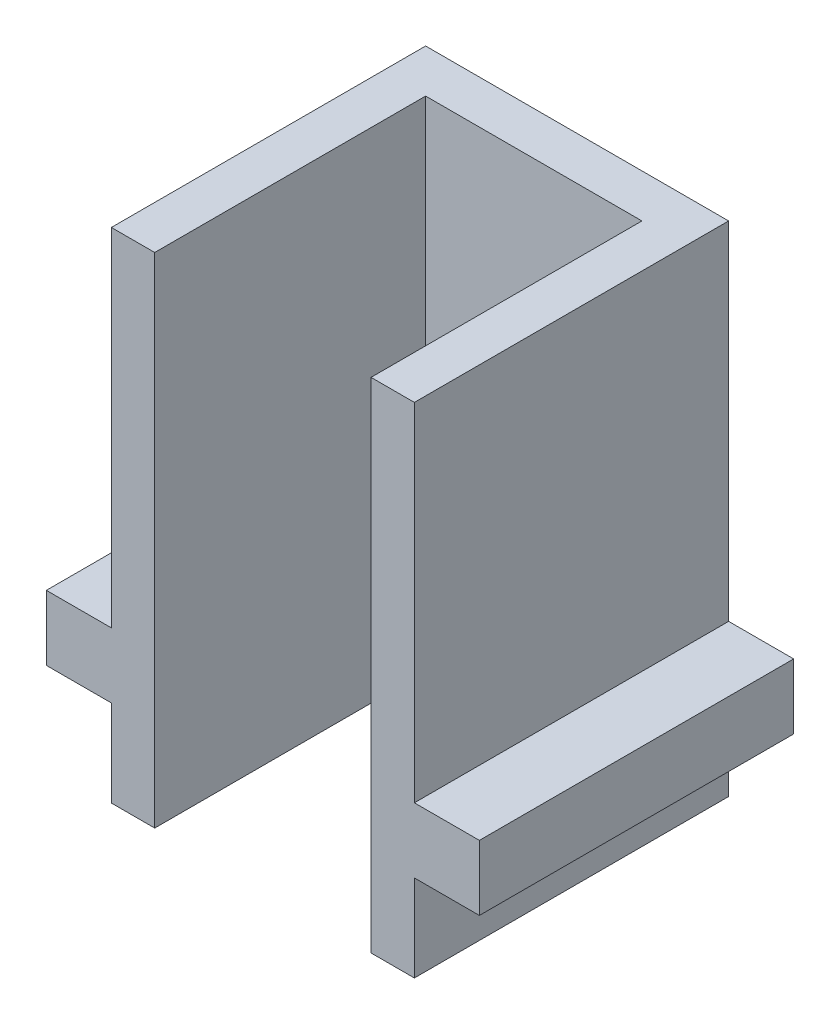
SolidWorks part; units mm, degrees
ref_plane "Front Plane" through (0, 0, 0) normal (0, 0, 1) x (1, 0, 0)
ref_plane "Top Plane" through (0, 0, 0) normal (0, 1, 0) x (1, 0, 0)
ref_plane "Right Plane" through (0, 0, 0) normal (1, 0, 0) x (0, 0, -1)
sketch "Sketch1" plane through (0, 0, 0) normal (0, 1, 0) x (1, 0, 0)
  line L0 (-4.99, 0) -> (4.99, 0)
  line L1 (4.99, 0) -> (4.99, -12.5)
  line L4 (4.99, -12.5) -> (6.99, -12.5)
  line L5 (6.99, -12.5) -> (6.99, 2)
  line L6 (6.99, 2) -> (-6.99, 2)
  line L7 (-6.99, 2) -> (-6.99, -12.5)
  line L8 (-6.99, -12.5) -> (-4.99, -12.5)
  line L11 (-4.99, -12.5) -> (-4.99, 0)
  point P13 (0, 0)
  dimension "D2" = 2
  dimension "D3" = 2
  dimension "D4" = 12.5
  dimension "D5" = 9.98
extrude "Boss-Extrude1" add sketch "Sketch1" along normal blind 23
sketch "Sketch9" plane through (-6.99, 0, 0) normal (-1, 0, 0) x (0, 0, 1)
  line L0 (12.5, 23) -> (12.5, 0) construction
  line L1 (-2, 7) -> (12.5, 7)
  line L2 (-2, 7) -> (-2, 4)
  line L3 (-2, 4) -> (12.5, 4)
  line L4 (12.5, 7) -> (12.5, 4)
  line L5 (-2, 7) -> (12.5, 4) construction
  line L6 (-2, 4) -> (12.5, 7) construction
  line L7 (-2, 23) -> (-2, 0) construction
  line L8 (-2, 0) -> (12.5, 0) construction
  point P0 (5.25, 5.5)
  dimension "D1" = 3
  dimension "D2" = 4
extrude "Boss-Extrude4" add sketch "Sketch9" along normal blind 3
ref_plane "Plane1" through (0, 0, 0) normal (-1, 0, 0) x (0, 0, 1)
mirror "Mirror1" about plane through (0, 0, 0) normal (-1, 0, 0) of "Boss-Extrude4"
